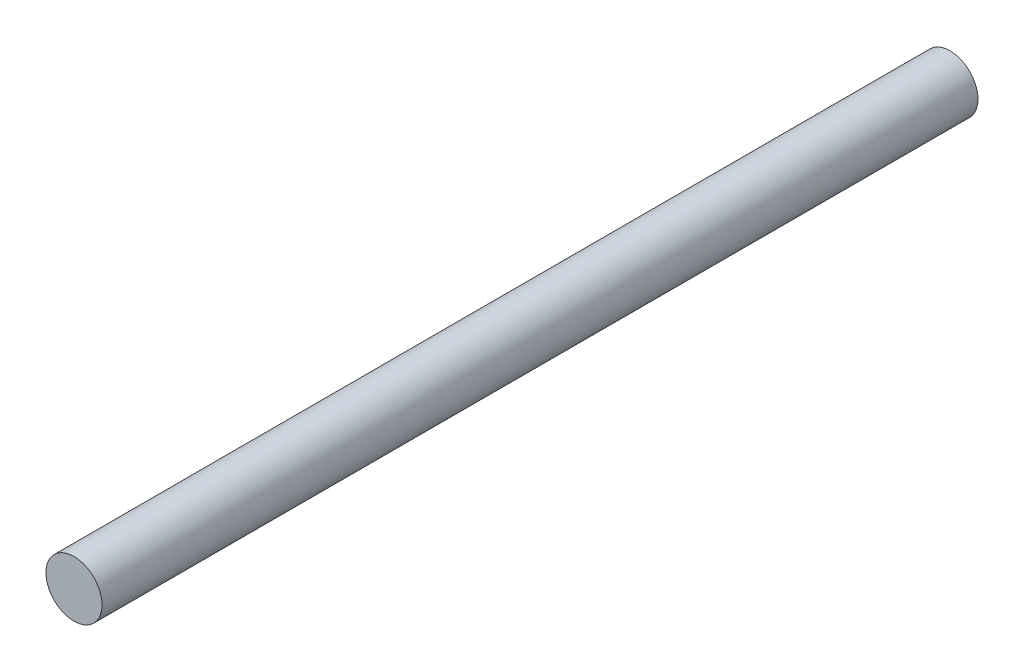
SolidWorks part; units mm, degrees
material "AISI 1020 Steel, Cold Rolled"
ref_plane "Front Plane" through (0, 0, 0) normal (0, 0, 1) x (1, 0, 0)
ref_plane "Top Plane" through (0, 0, 0) normal (0, 1, 0) x (1, 0, 0)
ref_plane "Right Plane" through (0, 0, 0) normal (1, 0, 0) x (0, 0, -1)
sketch "Sketch1" plane through (0, 0, 0) normal (0, 0, 1) x (1, 0, 0)
  circle A0 centre (0, 0) radius 8
  dimension "D1" = 16
extrude "Boss-Extrude1" add sketch "Sketch1" along normal blind 250
ref_plane "Плоскость1" through (0, 0, 0) normal (1, 0, 0) x (0, 0, -1)
equation "\"SBR16.Length.X\"= 600мм"
equation "\"SBR16.Length.Y\"= 500мм"
equation "\"SBR16.Length.Z\"= 250мм"
equation "\"D1@Boss-Extrude1\" = \"SBR16.Length.Z\""
